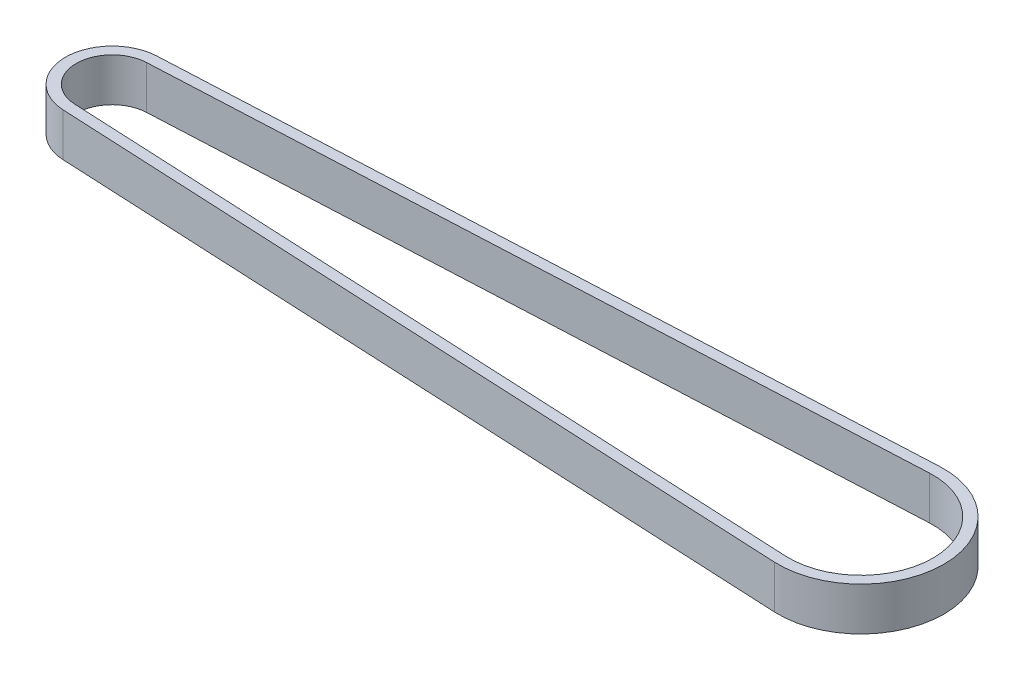
SolidWorks part; units mm, degrees
ref_plane "Front Plane" through (0, 0, 0) normal (0, 0, 1) x (1, 0, 0)
ref_plane "Top Plane" through (0, 0, 0) normal (0, 1, 0) x (1, 0, 0)
ref_plane "Right Plane" through (0, 0, 0) normal (1, 0, 0) x (0, 0, -1)
other "Default"
sketch "Sketch1" plane through (0, 0, 0) normal (0, 1, 0) x (1, 0, 0)
  line L0 (-0.2404, 4.9942) -> (103.4991, 9.9884)
  line L1 (103.4991, -9.9884) -> (-0.2404, -4.9942)
  line L2 (-0.3126, 6.4925) -> (103.427, 11.4867)
  line L3 (103.427, -11.4867) -> (-0.3126, -6.4925)
  arc A0 (-0.2404, 4.9942) -> (-0.2404, -4.9942) centre (0, 0) ccw
  arc A1 (103.4991, 9.9884) -> (103.4991, -9.9884) centre (103.98, 0) cw
  arc A2 (103.427, 11.4867) -> (103.427, -11.4867) centre (103.98, 0) cw
  arc A3 (-0.3126, 6.4925) -> (-0.3126, -6.4925) centre (0, 0) ccw
  dimension "R1" = 5
  dimension "R2" = 10
  dimension "CenterDistance" = 103.98
  dimension "Thickness" = 1.5
extrude "Boss-Extrude1" add sketch "Sketch1" along normal mid plane 6
